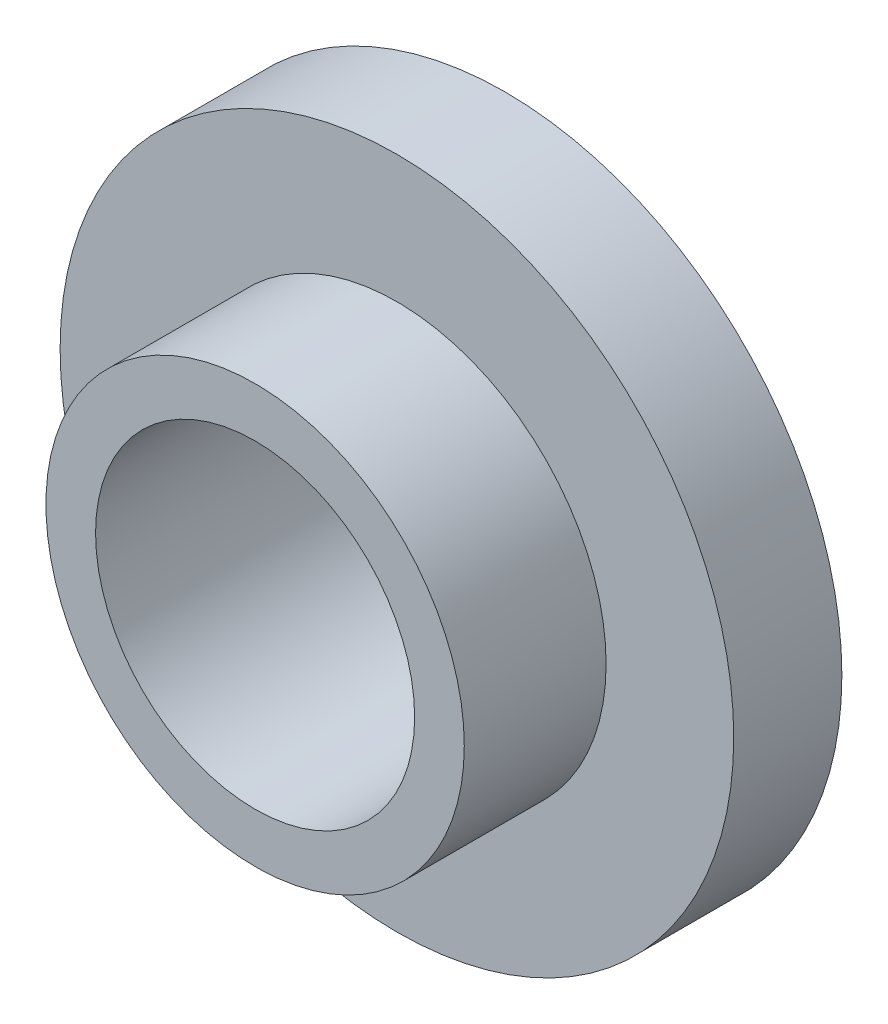
SolidWorks part; units mm, degrees
ref_plane "Piano frontale" through (0, 0, 0) normal (0, 0, 1) x (1, 0, 0)
ref_plane "Piano superiore" through (0, 0, 0) normal (0, 1, 0) x (1, 0, 0)
ref_plane "Piano destro" through (0, 0, 0) normal (1, 0, 0) x (0, 0, -1)
sketch "Schizzo1" plane through (0, 0, 0) normal (0, 0, 1) x (1, 0, 0)
  circle A0 centre (0, 0) radius 4.5
  circle A1 centre (0, 0) radius 5.9
extrude "Estrusione-Estrusione1" add sketch "Schizzo1" along normal blind 4 contours A1 | A0
sketch "Schizzo2" plane through (0, 0, 0) normal (0, 0, -1) x (-1, 0, 0)
  circle A0 centre (0, 0) radius 9.5
  circle A1 centre (0, 0) radius 4.5
extrude "Estrusione-Estrusione2" add sketch "Schizzo2" along normal blind 4 contours A0 | A1
sketch "Schizzo3" plane through (0, 0, -4) normal (0, 0, -1) x (-1, 0, 0)
  circle A0 centre (0, 0) radius 9.5
extrude "Taglio-Estrusione1" cut sketch "Schizzo3" against normal blind 0.95
